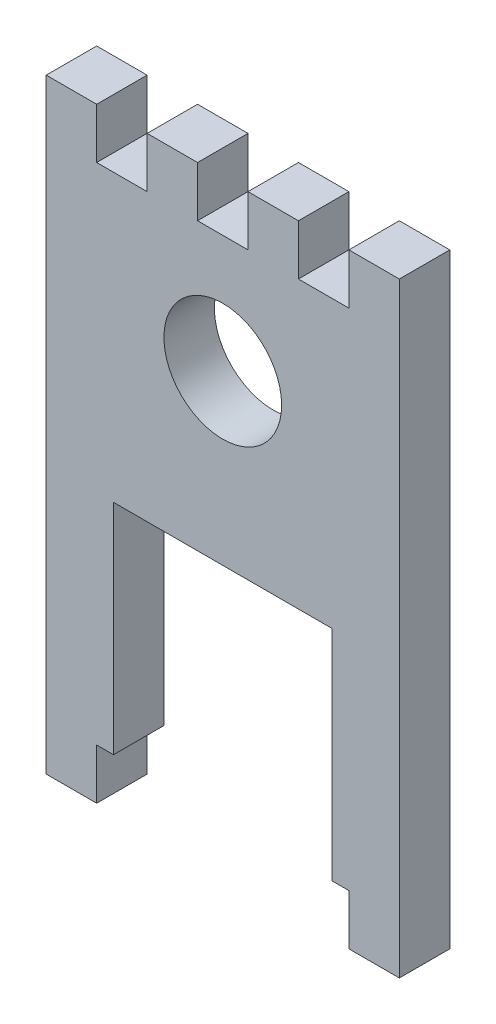
SolidWorks part; units mm, degrees
ref_plane "Front Plane" through (0, 0, 0) normal (0, 0, 1) x (1, 0, 0)
ref_plane "Top Plane" through (0, 0, 0) normal (0, 1, 0) x (1, 0, 0)
ref_plane "Right Plane" through (0, 0, 0) normal (1, 0, 0) x (0, 0, -1)
sketch "Sketch2" plane through (0, 0, 0) normal (0, 0, 1) x (1, 0, 0)
  line L0 (0.5337, 10.71) -> (0.5337, -6.29) construction
  line L1 (-9.9663, 13.71) -> (-6.9663, 13.71)
  line L2 (-9.9663, 13.71) -> (-9.9663, -22.29)
  line L3 (-9.9663, -22.29) -> (-6.9663, -22.29)
  line L4 (11.0337, 13.71) -> (11.0337, -22.29)
  line L5 (-6.9663, -19.29) -> (-5.9663, -19.29)
  line L6 (-6.9663, -19.29) -> (-6.9663, -22.29)
  line L9 (-9.9663, -4.29) -> (11.0337, -4.29) construction
  line L12 (8.0337, -19.29) -> (7.0337, -19.29)
  line L13 (8.0337, -19.29) -> (8.0337, -22.29)
  line L14 (8.0337, 10.71) -> (8.0337, 13.71)
  line L19 (8.0337, 10.71) -> (5.0337, 10.71)
  line L20 (5.0337, 10.71) -> (5.0337, 13.71)
  line L23 (2.0337, 10.71) -> (2.0337, 13.71)
  line L24 (-0.9663, 10.71) -> (2.0337, 10.71)
  line L25 (-0.9663, 10.71) -> (-0.9663, 13.71)
  line L27 (-3.9663, 10.71) -> (-3.9663, 13.71)
  line L28 (-6.9663, 10.71) -> (-3.9663, 10.71)
  line L29 (-6.9663, 10.71) -> (-6.9663, 13.71)
  line L30 (2.0337, 13.71) -> (5.0337, 13.71)
  line L31 (-3.9663, 13.71) -> (-0.9663, 13.71)
  line L32 (8.0337, 13.71) -> (11.0337, 13.71)
  line L35 (8.0337, -22.29) -> (11.0337, -22.29)
  line L37 (-5.9663, -6.29) -> (7.0337, -6.29)
  line L38 (-5.9663, -6.29) -> (-5.9663, -19.29)
  line L40 (7.0337, -6.29) -> (7.0337, -19.29)
  circle A0 centre (0.5337, 3.71) radius 3.5
  dimension "D3" = 7
  dimension "D1" = 21
  dimension "D2" = 36
  dimension "D4" = 0
  dimension "D5" = 13
  dimension "D6" = 3
  dimension "D7" = 10
  dimension "D9" = 13
  dimension "D11" = 6.5
extrude "Boss-Extrude1" add sketch "Sketch2" along normal blind 3
